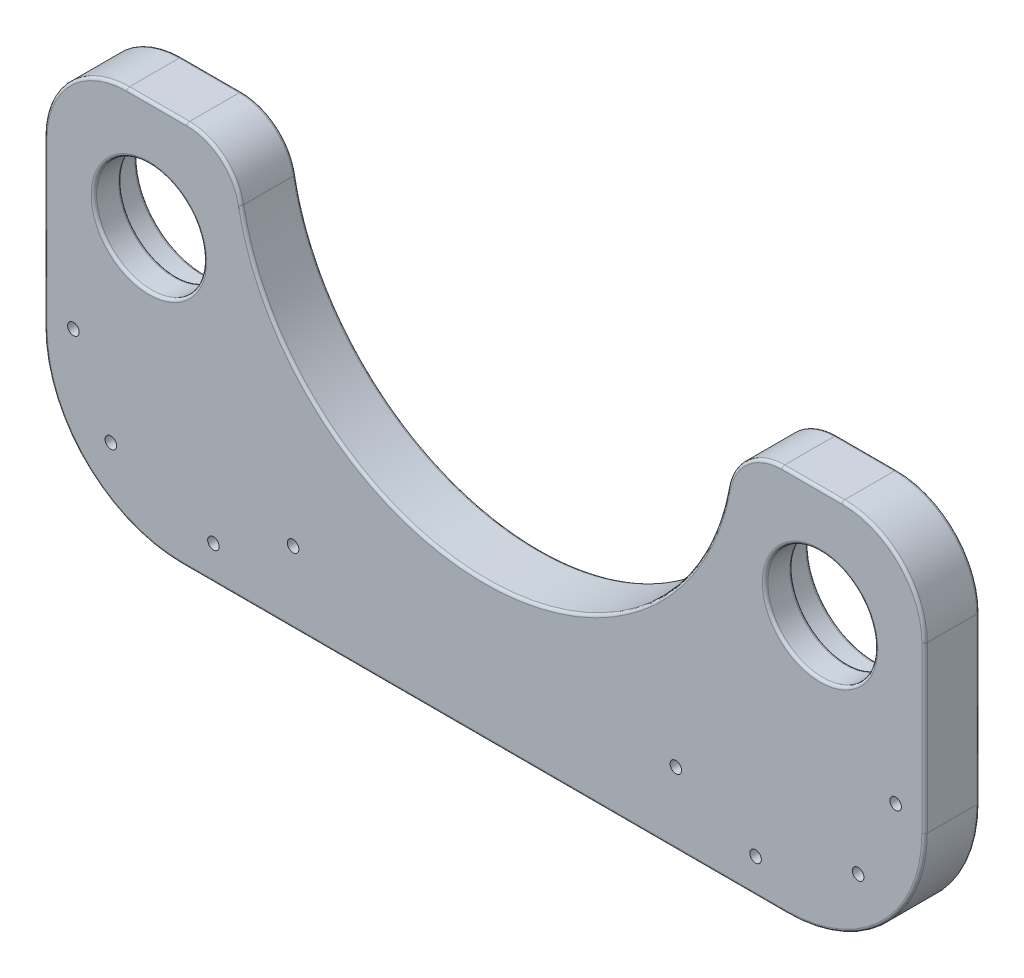
SolidWorks part; units mm, degrees
ref_plane "Front" through (0, 0, 0) normal (0, 0, 1) x (1, 0, 0)
ref_plane "Top" through (0, 0, 0) normal (0, 1, 0) x (1, 0, 0)
ref_plane "Right" through (0, 0, 0) normal (1, 0, 0) x (0, 0, -1)
sketch "Sketch1" plane through (0, 0, 0) normal (0, 0, 1) x (1, 0, 0)
  line L0 (134.0833, 70) -> (145, 70)
  line L1 (25, 0) -> (135, 0)
  line L2 (0, 25) -> (0, 55)
  line L3 (15, 70) -> (25.9167, 70)
  line L4 (160, 25) -> (160, 55)
  line L5 (80, 70) -> (80, 0) construction
  arc A0 (145, 70) -> (160, 55) centre (145, 55) cw
  arc A1 (135, 0) -> (160, 25) centre (135, 25) ccw
  arc A2 (25, 0) -> (0, 25) centre (25, 25) cw
  arc A3 (0, 55) -> (15, 70) centre (15, 55) cw
  arc A4 (35.7501, 61.8182) -> (25.9167, 70) centre (25.9167, 60) ccw
  arc A5 (124.2499, 61.8182) -> (134.0833, 70) centre (134.0833, 60) cw
  circle A6 centre (19, 50) radius 12.075
  circle A7 centre (141, 50) radius 12.075
  ellipse E0 centre (80, 70) end of major axis (80, 115) minor radius 45 (35.7501, 61.8182) -> (124.2499, 61.8182) ccw
  point P9 (160, 0)
  point P12 (0, 0)
  point P15 (0, 70)
  point P24 (80, 0)
  dimension "D3" = 15
  dimension "D6" = 10
  dimension "D7" = 10
  dimension "D8" = 61
  dimension "D9" = 24.15
  dimension "D11" = 25
  dimension "D1" = 160
  dimension "D2" = 70
  dimension "D4" = 25
  dimension "D5" = 45
  dimension "D10" = 50
extrude "Boss-Extrude1" add sketch "Sketch1" along normal blind 10
sketch "Sketch2" plane through (0, 0, 0) normal (0, 0, -1) x (-1, 0, 0)
  line L0 (-25, 0) -> (-135, 0) construction
  line L1 (-115, 0) -> (-45, 0)
  line L2 (-115, 0) -> (-115, 5)
  line L3 (-115, 5) -> (-45, 5)
  line L4 (-45, 0) -> (-45, 5)
  point P6 (-80, 0)
  dimension "D1" = 5
  dimension "D2" = 70
sketch "Sketch6" plane through (0, 0, 10) normal (0, 0, 1) x (1, 0, 0)
  circle A0 centre (141, 50) radius 12.075 construction
  circle A1 centre (19, 50) radius 12.075 construction
  circle A2 centre (141, 50) radius 12.075
  circle A3 centre (19, 50) radius 12.075
  circle A4 centre (19, 50) radius 10
  circle A5 centre (141, 50) radius 10
  dimension "D1" = 20
  dimension "D2" = 20
extrude "Boss-Extrude5" add sketch "Sketch6" against normal blind 5
fillet "Fillet3" radius 0.5 12 edges at (160, 40, 10) (152.6777, 7.3223, 10) (80, 0, 10) (7.3223, 7.3223, 10) (0, 40, 10) (4.3934, 65.6066, 10) (20.4584, 70, 10) (32.3128, 67.6871, 10) (80, 25, 10) (127.6872, 67.6871, 10) (139.5416, 70, 10) (155.6066, 65.6066, 10)
fillet "Fillet4" radius 0.5 8 edges at (31.075, 50, 5) (31.075, 50, 0) (153.075, 50, 5) (128.925, 50, 0) (151, 50, 5) (29, 50, 5) (29, 50, 10) (151, 50, 10)
sketch "Sketch10" plane through (0, 0, 10) normal (0, 0, 1) x (1, 0, 0)
  line L0 (80, 24.5) -> (80, 0.5) construction
  line L1 (25, 0.5) -> (135, 0.5) construction
  circle A0 centre (5.2731, 27.2504) radius 1.05
  circle A1 centre (12.0789, 12.77) radius 1.05
  circle A2 centre (30.731, 6.2331) radius 1.05
  circle A3 centre (45.2113, 13.0389) radius 1.05
  arc A4 (35.2584, 61.7273) -> (124.7416, 61.7273) centre (80, 70) ccw construction
  circle A5 centre (114.7887, 13.0389) radius 1.05
  circle A6 centre (129.269, 6.2331) radius 1.05
  circle A7 centre (147.9211, 12.77) radius 1.05
  circle A8 centre (154.7269, 27.2504) radius 1.05
  dimension "D1" = 2.1
  dimension "D2" = 2.1
  dimension "D3" = 2.1
  dimension "D4" = 2.1
extrude "Cut-Extrude3" cut sketch "Sketch10" against normal through all
extrude "Boss-Extrude6" add sketch "Sketch2" along normal blind 20
sketch "Sketch11" plane through (0, 5, 0) normal (0, 1, 0) x (1, 0, 0)
  line L0 (45, 0) -> (115, 0) construction
  line L1 (45, 20) -> (115, 20) construction
  line L2 (80, 20) -> (80, 0) construction
  circle A0 centre (100, 10) radius 2.575
  circle A2 centre (60, 10) radius 2.575
  point P8 (80, 20)
  dimension "D1" = 5.15
  dimension "D2" = 10
  dimension "D3" = 20
extrude "Cut-Extrude4" cut sketch "Sketch11" against normal through all
fillet "Fillet5" radius 0.5 24 edges at (80, 25, 0) (32.3128, 67.6871, 0) (127.6872, 67.6871, 0) (20.4584, 70, 0) (139.5416, 70, 0) (4.3934, 65.6066, 0) (155.6066, 65.6066, 0) (0, 40, 0) (160, 40, 0) (7.3223, 7.3223, 0) (152.6777, 7.3223, 0) (35, 0, 0) (125, 0, 0) (45, 2.5, -20) (45, 0, -10) (45, 5, -10) (45, 2.5, 0) (80, 0, -20) (115, 2.5, -20) (115, 0, -10) (115, 2.5, 0) (115, 5, -10) (80, 5, 0) (80, 5, -20)
